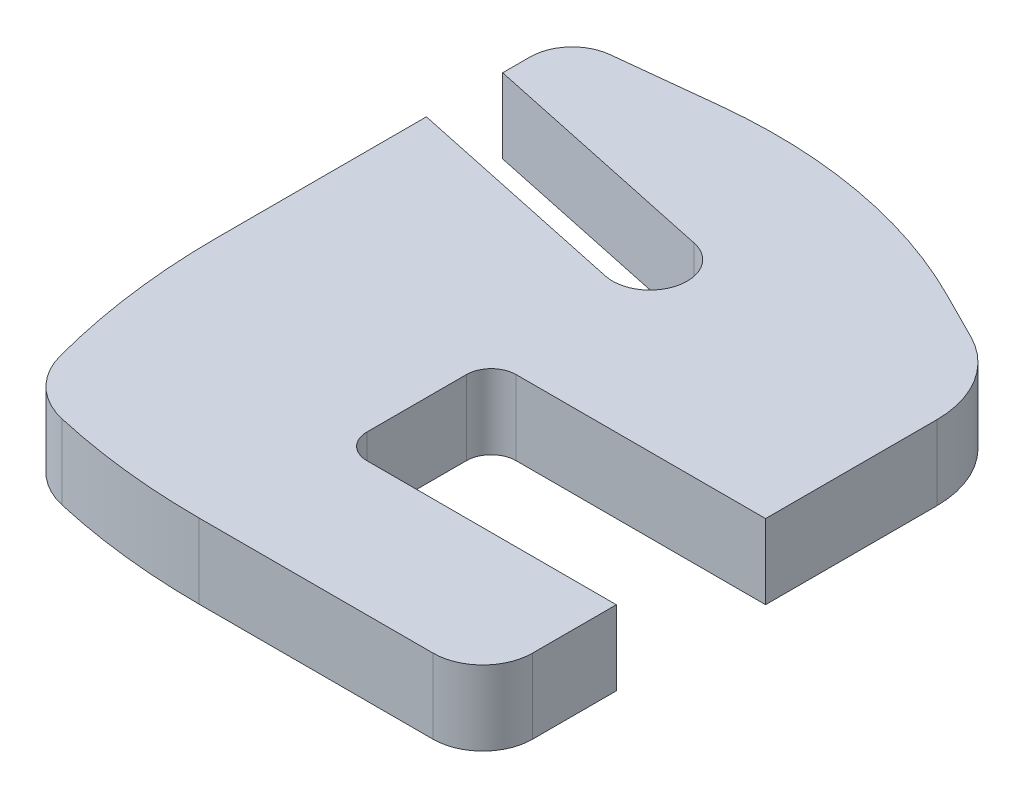
SolidWorks part; units mm, degrees
ref_plane "Front Plane" through (0, 0, 0) normal (0, 0, 1) x (1, 0, 0)
ref_plane "Top Plane" through (0, 0, 0) normal (0, 1, 0) x (1, 0, 0)
ref_plane "Right Plane" through (0, 0, 0) normal (1, 0, 0) x (0, 0, -1)
sketch "Sketch1" plane through (0, 0, 0) normal (0, 1, 0) x (1, 0, 0)
  line L0 (0, 6) -> (0, 12.8856)
  line L1 (-20.81, 17.3383) -> (-20.81, 16.2388)
  line L2 (-20.81, 16.2388) -> (-11.03, 14.16)
  line L3 (-11.6537, 11.2256) -> (-20.81, 13.1718)
  line L4 (-20.81, 13.1718) -> (-20.81, 4.7668)
  line L5 (-11.405, -5.37) -> (-2, -5.37)
  line L6 (0, -3.37) -> (0, 0)
  line L7 (0, 0) -> (-10.03, 0)
  line L8 (-11.03, 1) -> (-11.03, 5)
  line L9 (-10.03, 6) -> (0, 6)
  line L10 (-2.2011, 16.4583) -> (-4.1545, 17.4418)
  line L11 (-15.3099, 19.4613) -> (-19.2937, 19.0284)
  arc A1 (-11.03, 14.16) -> (-11.6537, 11.2256) centre (-11.3419, 12.6928) cw
  arc A2 (-4.1545, 17.4418) -> (-15.3099, 19.4613) centre (-13.1489, -0.4216) ccw
  arc A3 (-19.2937, 19.0284) -> (-20.81, 17.3383) centre (-19.11, 17.3383) ccw
  arc A4 (0, 12.8856) -> (-2.2011, 16.4583) centre (-4, 12.8856) ccw
  arc A5 (-11.03, 5) -> (-10.03, 6) centre (-10.03, 5) cw
  arc A6 (-10.03, 0) -> (-11.03, 1) centre (-10.03, 1) cw
  arc A7 (-2, -5.37) -> (0, -3.37) centre (-2, -3.37) ccw
  arc A8 (-19.8425, -2.53) -> (-20.81, 4.7668) centre (7.19, 4.7668) cw
  arc A9 (-17.6111, -4.6736) -> (-11.405, -5.37) centre (-11.405, 22.63) ccw
  arc A10 (-19.8425, -2.53) -> (-17.6111, -4.6736) centre (-16.9462, -1.7482) ccw
  point P17 (-9.4338, 20.1)
  point P22 (0, 15.35)
  dimension "D7" = 1.5
  dimension "D8" = 20
  dimension "D9" = 1.7
  dimension "D10" = 4
  dimension "D12" = 1
  dimension "D13" = 2
  dimension "D14" = 28
  dimension "D15" = 3
  dimension "D1" = 25.47
  dimension "D2" = 12
  dimension "D3" = 6
  dimension "D4" = 5.37
  dimension "D5" = 9.35
  dimension "D6" = 11.03
  dimension "D11" = 20.81
  dimension "D16" = 13.4613
  dimension "D17" = 14.16
  dimension "D18" = 7.6611
  dimension "D19" = 16.9462
  dimension "D20" = 1.7482
extrude "Boss-Extrude1" add sketch "Sketch1" along normal blind 3
